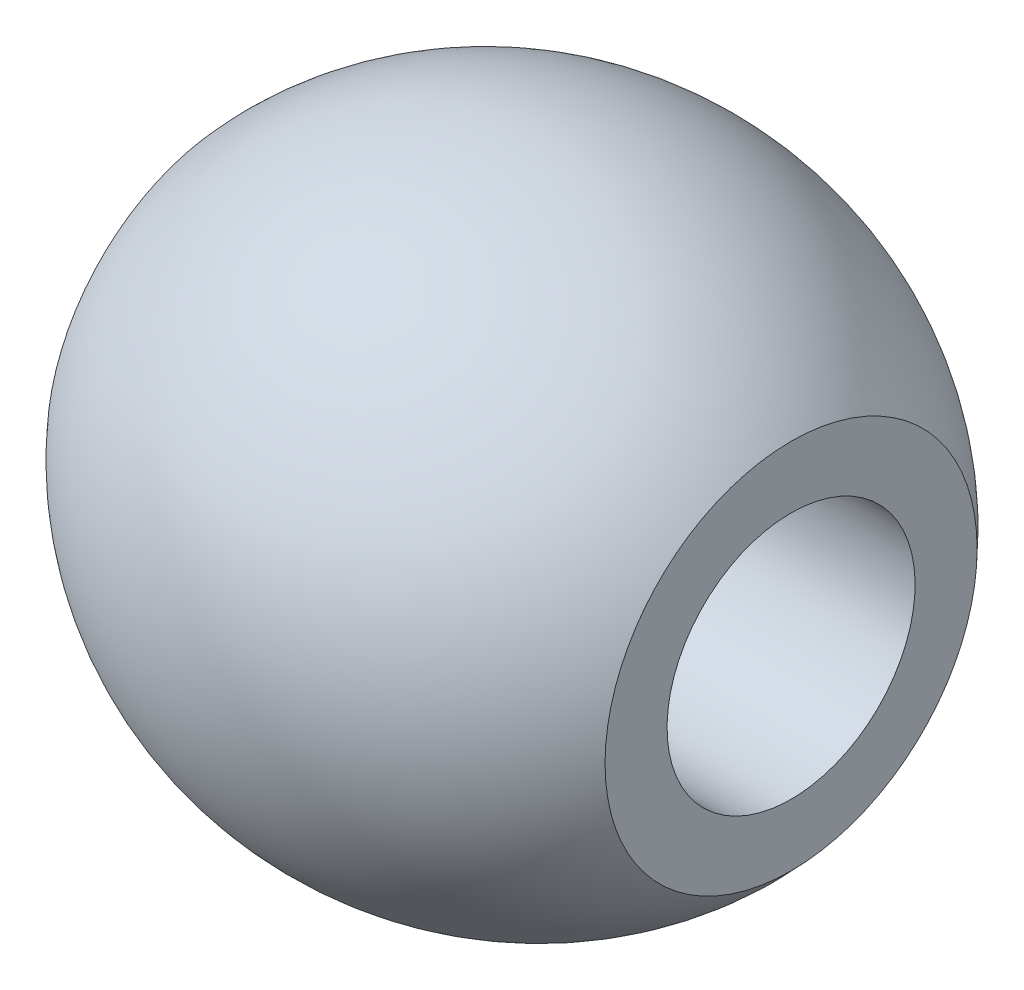
SolidWorks part; units mm, degrees
material "AISI 316 Annealed Stainless Steel Bar (SS)"
ref_plane "Front Plane" through (0, 0, 0) normal (0, 0, 1) x (1, 0, 0)
ref_plane "Top Plane" through (0, 0, 0) normal (0, 1, 0) x (1, 0, 0)
ref_plane "Right Plane" through (0, 0, 0) normal (1, 0, 0) x (0, 0, -1)
sketch "Sketch1" plane through (0, 0, 0) normal (0, 0, 1) x (1, 0, 0)
  line L0 (1000, 0) -> (4, 0) construction
  line L1 (-5, 0) -> (4, 0)
  line L2 (-5, 3) -> (-5, 0)
  line L3 (4, 3) -> (4, 0)
  line L5 (-5, 3) -> (49995, 3) construction
  line L9 (-5, 0) -> (-14351.929, 0) construction
  arc A0 (-5, 3) -> (4, 3) centre (-0.5, -0.9686) cw
  dimension "D4" = 0.9686
  dimension "D1" = 9
  dimension "D2" = 3
  dimension "D3" = 5
revolve "Revolve2" add sketch "Sketch1" angle 360 about L1
sketch "Sketch2" plane through (0, 0, 0) normal (0, 0, 1) x (1, 0, 0)
  line L0 (-5, 0) -> (49995, 0) construction
  line L1 (-5, 3) -> (-5, -3) construction
  line L2 (4, -3) -> (4, 3) construction
  line L3 (-0.3553, 2) -> (-50000.3553, 2) construction
  line L4 (-5, 3) -> (-4, 2)
  line L5 (-4, 2) -> (4, 2)
  line L6 (4, 2) -> (4, 0)
  line L7 (4, 0) -> (-5, 0)
  line L8 (-5, 3) -> (-5, 0)
  point P4 (-5, 0)
  point P7 (4, 0)
  dimension "D1" = 2
  dimension "D2" = 45
revolve "Cut-Revolve1" cut sketch "Sketch2" angle 360 about L7
